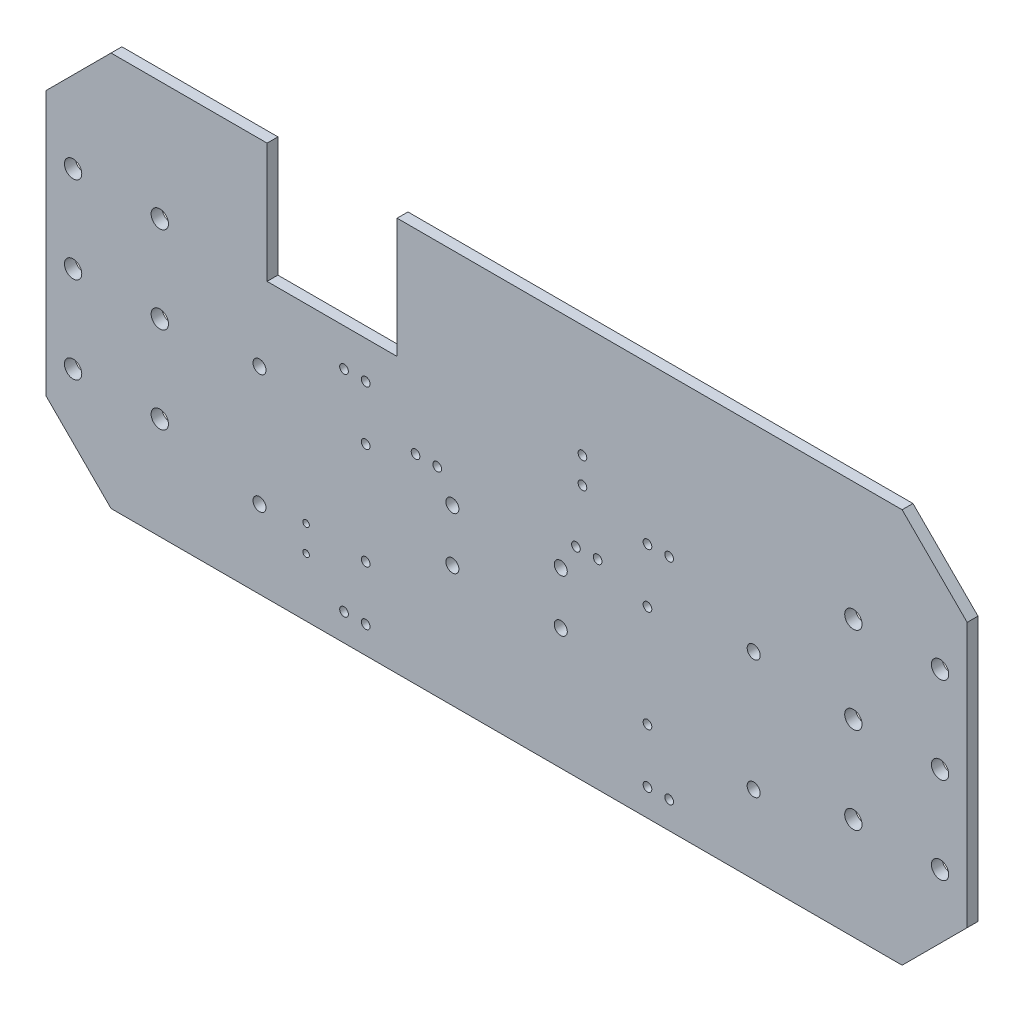
SolidWorks part; units mm, degrees
material "Thornel Mat VMA"
ref_plane "前视基准面" through (0, 0, 0) normal (0, 0, 1) x (1, 0, 0)
ref_plane "上视基准面" through (0, 0, 0) normal (0, 1, 0) x (1, 0, 0)
ref_plane "右视基准面" through (0, 0, 0) normal (1, 0, 0) x (0, 0, -1)
sketch "草图1" plane through (0, 0, 0) normal (0, 0, 1) x (1, 0, 0)
  line L1 (-212.5, 91) -> (212.5, 91)
  line L2 (-212.5, 91) -> (-212.5, -91)
  line L3 (-212.5, -91) -> (212.5, -91)
  line L4 (212.5, 91) -> (212.5, -91)
  point P4 (0, 91)
  point P6 (212.5, 0)
  dimension "D1" = 182
  dimension "D2" = 425
extrude "凸台-拉伸1" add sketch "草图1" along normal blind 5
sketch "草图2" plane through (0, 0, 0) normal (0, 0, 1) x (1, 0, 0)
  line L0 (0, 82.4144) -> (0, -82.4144) construction
  line L1 (-212.5, -91) -> (212.5, -91) construction
  line L2 (-25, -11) -> (25, -35) construction
  line L3 (-92.5, -52) -> (-92.5, -64) construction
  line L5 (-200, 36) -> (-160, -4) construction
  line L8 (200, 36) -> (160, -4) construction
  line L9 (-212.5, 91) -> (-212.5, -91) construction
  line L10 (212.5, 91) -> (-212.5, 91) construction
  circle A16 centre (-25, -11) radius 3
  circle A17 centre (-25, -35) radius 3
  circle A18 centre (25, -35) radius 3
  circle A19 centre (25, -11) radius 3
  circle A20 centre (-200, 36) radius 4
  circle A21 centre (-160, 36) radius 4
  circle A22 centre (-200, -4) radius 4
  circle A23 centre (-160, -4) radius 4
  circle A24 centre (160, -4) radius 4
  circle A25 centre (200, -4) radius 4
  circle A26 centre (160, 36) radius 4
  circle A27 centre (200, 36) radius 4
  circle A28 centre (-200, -44) radius 4
  circle A29 centre (-160, -44) radius 4
  circle A30 centre (160, -44) radius 4
  circle A31 centre (200, -44) radius 4
  circle A32 centre (-32, 1) radius 2
  circle A33 centre (-42, 1) radius 2
  circle A34 centre (32, 1) radius 2
  circle A35 centre (42, 1) radius 2
  circle A38 centre (35, 39) radius 2
  circle A39 centre (35, 27) radius 2
  circle A40 centre (-75, -78.5) radius 2
  circle A41 centre (-65, -78.5) radius 2
  circle A42 centre (-65, -53.5) radius 2
  circle A43 centre (-65, -6.5) radius 2
  circle A44 centre (-65, 18.5) radius 2
  circle A45 centre (-75, 18.5) radius 2
  circle A46 centre (75, -78.5) radius 2
  circle A47 centre (65, -78.5) radius 2
  circle A48 centre (65, -53.5) radius 2
  circle A49 centre (65, -6.5) radius 2
  circle A50 centre (65, 18.5) radius 2
  circle A51 centre (75, 18.5) radius 2
  circle A52 centre (-114, -55) radius 3
  circle A53 centre (-114, 0) radius 3
  circle A54 centre (114, 0) radius 3
  circle A55 centre (114, -55) radius 3
  circle A56 centre (-92.5, -52) radius 1.5
  circle A57 centre (-92.5, -64) radius 1.5
  point P16 (-92.5, -58)
  point P32 (180, 16)
  point P48 (0, 0)
  point P61 (-180, 16)
  dimension "D5" = 6
  dimension "D11" = 8
  dimension "D17" = 4
  dimension "D21" = 52
  dimension "D27" = 4
  dimension "D30" = 4
  dimension "D33" = 25
  dimension "D7" = 6
  dimension "D24" = 3
  dimension "D4" = 36
  dimension "D6" = 98.5
  dimension "D8" = 92
  dimension "D9" = 24
  dimension "D10" = 50
  dimension "D12" = 40
  dimension "D13" = 40
  dimension "D14" = 360
  dimension "D15" = 56
  dimension "D16" = 40
  dimension "D18" = 10
  dimension "D19" = 55
  dimension "D20" = 64
  dimension "D22" = 47
  dimension "D23" = 12
  dimension "D25" = 12
  dimension "D26" = 35
  dimension "D28" = 12.5
  dimension "D29" = 137.5
  dimension "D31" = 10
  dimension "D32" = 25
  dimension "D34" = 47
  dimension "D35" = 33
  dimension "D36" = 120
extrude "切除-拉伸2" cut sketch "草图2" along normal through all
sketch "草图3" plane through (0, 0, 5) normal (0, 0, 1) x (1, 0, 0)
  line L0 (212.5, 91) -> (-212.5, 91) construction
  line L1 (-50.5, 91) -> (-110.5, 91)
  line L2 (-50.5, 91) -> (-50.5, 35.75)
  line L3 (-50.5, 35.75) -> (-110.5, 35.75)
  line L4 (-110.5, 91) -> (-110.5, 35.75)
  line L5 (-212.5, 91) -> (-212.5, -91) construction
  dimension "D1" = 162
  dimension "D2" = 55.25
  dimension "D3" = 60
extrude "切除-拉伸3" cut sketch "草图3" against normal blind 10
chamfer "倒角1" distance 30 angle 45 4 edges at (212.5, -91, 2.5) (212.5, 91, 2.5) (-212.5, -91, 2.5) (-212.5, 91, 2.5)
